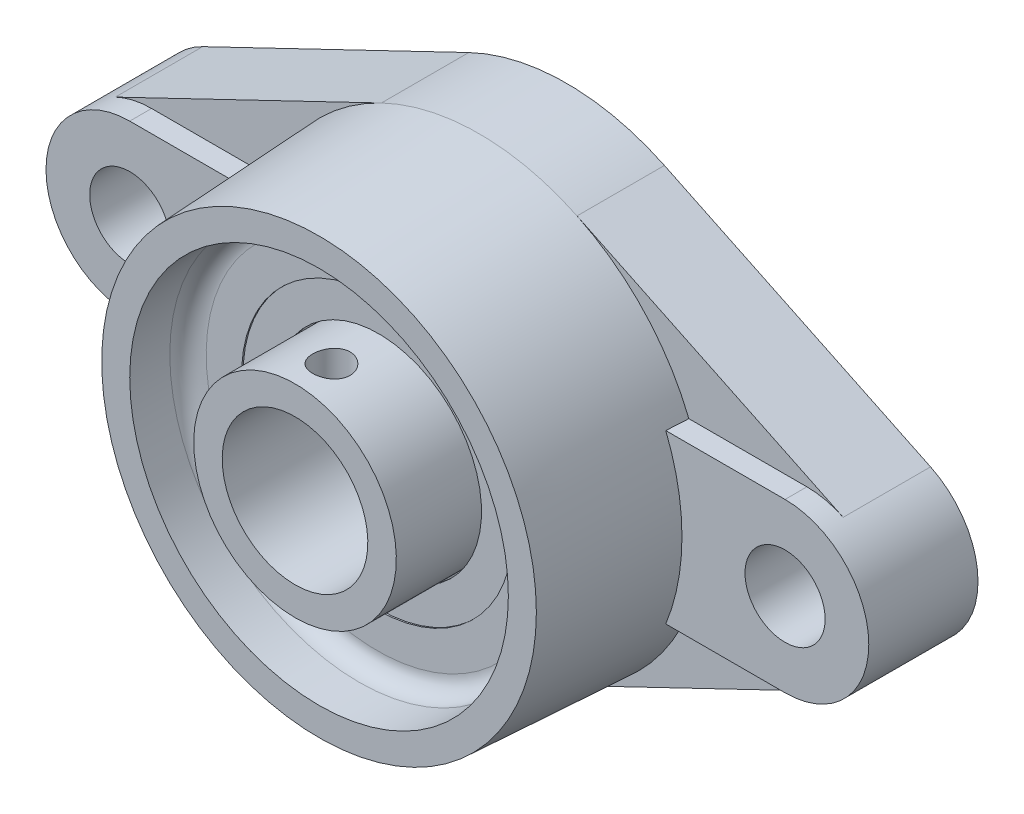
SolidWorks part; units mm, degrees
ref_plane "前视" through (0, 0, 0) normal (0, 0, 1) x (1, 0, 0)
ref_plane "上视" through (0, 0, 0) normal (0, 1, 0) x (1, 0, 0)
ref_plane "右视" through (0, 0, 0) normal (1, 0, 0) x (0, 0, -1)
sketch "尺寸草图" plane through (0, 0, 0) normal (0, 0, 1) x (1, 0, 0)
  line L0 (0, 0) -> (0, -31) construction
  line L1 (0, 0) -> (-56.5, 0) construction
  line L2 (0, 0) -> (47, 0) construction
  line L3 (49, 0) -> (80, 0) construction
  circle A0 centre (0, 0) radius 31
  circle A1 centre (-45, 0) radius 5.5
  point P8 (15, 0)
  point P9 (19, 0)
  point P10 (49, 0)
  point P11 (-14, 0)
  point P14 (50, 0)
  point P15 (67.3, 0)
  point P16 (69, 0)
  point P17 (54, 0)
  point P18 (60, 0)
  dimension "L" = 62
  dimension "N" = 11
  dimension "H" = 113
  dimension "J" = 90
  dimension "Da" = 47
  dimension "A1" = 15
  dimension "A2" = 19
  dimension "A" = 34
  dimension "C" = 14
  dimension "ucB" = 31
  dimension "ucP" = 1
  dimension "ucd" = 20
  dimension "ucG" = 5
  dimension "ucDs" = 6
  dimension "ucS" = 12.7
sketch "草图2" plane through (0, 0, 0) normal (0, 0, 1) x (1, 0, 0)
  line L0 (0, 0) -> (0, -31) construction
  line L1 (0, 0) -> (0, -31) construction
  line L2 (-49.9833, 10.3642) -> (-13.4333, 27.9382)
  line L3 (-49.9833, -10.3642) -> (-13.4333, -27.9382)
  line L4 (0, 0) -> (-56.5, 0) construction
  line L5 (49.9833, 10.3642) -> (13.4333, 27.9382)
  line L6 (49.9833, -10.3642) -> (13.4333, -27.9382)
  circle A0 centre (-45, 0) radius 5.5 construction
  circle A1 centre (0, 0) radius 31 construction
  circle A2 centre (-45, 0) radius 5.5
  arc A3 (13.4333, 27.9382) -> (-13.4333, 27.9382) centre (0, 0) ccw
  circle A4 centre (45, 0) radius 5.5
  arc A5 (-49.9833, 10.3642) -> (-49.9833, -10.3642) centre (-45, 0) ccw
  arc A6 (49.9833, 10.3642) -> (49.9833, -10.3642) centre (45, 0) cw
  arc A7 (-13.4333, -27.9382) -> (13.4333, -27.9382) centre (0, 0) ccw
  dimension "D1" = 113
extrude "基体-拉伸" add sketch "草图2" along normal blind 12
sketch "草图3" plane through (0, 0, 0) normal (0, 0, 1) x (1, 0, 0)
  line L0 (-45, 11.5) -> (45, 11.5)
  line L1 (-45, -11.5) -> (45, -11.5)
  arc A0 (49.9833, -10.3642) -> (49.9833, 10.3642) centre (45, 0) ccw construction
  arc A1 (-49.9833, 10.3642) -> (-49.9833, -10.3642) centre (-45, 0) ccw construction
  arc A2 (45, -11.5) -> (45, 11.5) centre (45, 0) ccw
  arc A3 (-45, 11.5) -> (-45, -11.5) centre (-45, 0) ccw
  circle A4 centre (45, 0) radius 5.5 construction
  circle A5 centre (45, 0) radius 5.5
  circle A6 centre (-45, 0) radius 5.5 construction
  circle A7 centre (-45, 0) radius 5.5
extrude "凸台-拉伸1" add sketch "草图3" along normal blind 15
sketch "草图4" plane through (0, 0, 12) normal (0, 0, 1) x (1, 0, 0)
  circle A0 centre (0, 0) radius 31 construction
  circle A1 centre (0, 0) radius 31
extrude "凸台-拉伸2" add sketch "草图4" along normal blind 22 draft 3
sketch "草图5" plane through (0, 0, 0) normal (0, 0, -1) x (-1, 0, 0)
  line L0 (-34.9601, 11.7401) -> (-11.1497, 23.1887)
  line L1 (-49.9833, 10.3642) -> (-13.4333, 27.9382) construction
  line L2 (0, 31) -> (0, -31) construction
  line L3 (-34.9601, -11.7401) -> (-11.1497, -23.1887)
  line L4 (-45, 0) -> (45, 0) construction
  line L5 (34.9601, -11.7401) -> (11.1497, -23.1887)
  line L6 (34.9601, 11.7401) -> (11.1497, 23.1887)
  arc A0 (11.1497, 23.1887) -> (-11.1497, 23.1887) centre (0, 0) ccw
  arc A1 (-36.0063, 7.1668) -> (-36.0063, -7.1668) centre (-45, 0) cw
  arc A2 (-13.4333, -27.9382) -> (13.4333, -27.9382) centre (0, 0) ccw construction
  arc A3 (-49.9833, 10.3642) -> (-49.9833, -10.3642) centre (-45, 0) ccw construction
  arc A5 (11.1497, -23.1887) -> (-11.1497, -23.1887) centre (0, 0) cw
  arc A6 (-13.4333, -27.9382) -> (13.4333, -27.9382) centre (0, 0) ccw construction
  arc A7 (-36.0063, -7.1668) -> (-34.9601, -11.7401) centre (-33.6601, -9.0364) ccw
  arc A8 (36.0063, 7.1668) -> (34.9601, 11.7401) centre (33.6601, 9.0364) ccw
  arc A9 (-36.0063, 7.1668) -> (-34.9601, 11.7401) centre (-33.6601, 9.0364) cw
  arc A10 (36.0063, -7.1668) -> (34.9601, -11.7401) centre (33.6601, -9.0364) cw
  arc A11 (36.0063, 7.1668) -> (36.0063, -7.1668) centre (45, 0) ccw
  dimension "D1" = 25.73
  dimension "D2" = 3
extrude "切除-拉伸2" cut sketch "草图5" against normal blind 3
sketch "草图6" plane through (0, 0, 0) normal (1, 0, 0) x (0, 0, -1)
  line L0 (-34, 29.847) -> (-34, -29.847) construction
  line L1 (-36, 26) -> (-28.5, 26)
  line L2 (-9.5, 26) -> (2, 26)
  line L3 (-26, 22.4332) -> (-26, 23.5)
  line L4 (-23.6667, 25.2678) -> (-21.3333, 25.2678)
  line L5 (-23.6667, 25.2678) -> (-23.6667, 23.032)
  line L6 (-12, 22.4332) -> (-12, 23.5)
  line L7 (-21.3333, 25.2678) -> (-21.3333, 23.3839)
  line L8 (0, 0) -> (-34, 0) construction
  line L9 (-36, 26) -> (-36, 0)
  line L10 (-36, 0) -> (2, 0)
  line L11 (2, 0) -> (2, 26)
  line L12 (0, 10.3642) -> (0, 27.9382) construction
  line L13 (0, 27.9382) -> (0, 31) construction
  arc A0 (-26, 22.4332) -> (-23.6667, 23.032) centre (-19, 0) cw
  arc A1 (-21.3333, 23.3839) -> (-12, 22.4332) centre (-19, 0) cw
  arc A2 (-28.5, 26) -> (-26, 23.5) centre (-28.5, 23.5) cw
  arc A3 (-9.5, 26) -> (-12, 23.5) centre (-9.5, 23.5) ccw
  point P16 (-19, 23.5)
  point P17 (-26.7322, 25.2678)
  dimension "D3" = 23.5
  dimension "D1" = 19
  dimension "D2" = 14
  dimension "D4" = 26
  dimension "D5" = 2
  dimension "D6" = 2
revolve "切除-旋转1" cut sketch "草图6" angle 360 about L8
ref_plane "油嘴用面" through (0, 0, 18.5) normal (0, 0, 1) x (1, 0, 0)
sketch "草图7" plane through (0, 0, 18.5) normal (0, 0, 1) x (1, 0, 0)
  line L0 (-26.9827, -26.9827) -> (0, 0) construction
  line L2 (-21.6794, -21.6794) -> (-18.8509, -24.5079)
  line L3 (-18.8509, -24.5079) -> (-19.1566, -24.8137)
  line L4 (-25.4554, -27.5767) -> (-26.0494, -26.9827)
  line L5 (-26.9827, -26.9827) -> (-21.6794, -21.6794)
  line L6 (0, 0) -> (-22.4332, 0) construction
  circle A1 centre (0, 0) radius 22.4332 construction
  arc A4 (-19.1566, -24.8137) -> (-20.5217, -26.6375) centre (-13.4998, -30.4705) ccw
  arc A5 (-20.5217, -26.6375) -> (-25.4554, -27.5767) centre (-23.3744, -25.0803) cw
  arc A6 (-26.9827, -26.9827) -> (-26.0494, -26.9827) centre (-26.516, -26.516) ccw
  dimension "D4" = 8
  dimension "D5" = 3.25
  dimension "D7" = 0.66
  dimension "D1" = 1.5
  dimension "D2" = 4.0001
  dimension "D3" = 0.4323
  dimension "D6" = 45
  dimension "D8" = 7.5
  dimension "D9" = 30.6593
revolve "凸台-旋转1" add sketch "草图7" angle 360 about L5
sketch "草图8" plane through (0, 0, 0) normal (1, 0, 0) x (0, 0, -1)
  line L0 (-26, 22.4332) -> (-26, 18.64)
  line L1 (-26, 18.64) -> (-12, 18.64)
  line L2 (-12, 18.64) -> (-12, 22.4332)
  line L3 (-19, 0) -> (0, 0) construction
  arc A0 (-26, 22.4332) -> (-12, 22.4332) centre (-19, 0) cw
  arc A1 (-12, 22.4332) -> (-21.3333, 23.3839) centre (-19, 0) ccw construction
  dimension "D2" = 4.86
  dimension "D1" = 14
revolve "凸台-旋转2" add sketch "草图8" angle 360 about L3
sketch "草图9" plane through (0, 0, 0) normal (1, 0, 0) x (0, 0, -1)
  line L0 (-19, 0) -> (-19, 23.5) construction
  line L1 (-34, 0) -> (0, 0) construction
  line L2 (-19, 20.5975) -> (-19, 12.9025)
  line L3 (-34, 29.847) -> (-34, -29.847) construction
  arc A0 (-12, 22.4332) -> (-26, 22.4332) centre (-19, 0) ccw construction
  arc A1 (-19, 12.9025) -> (-19, 20.5975) centre (-19, 16.75) ccw
  dimension "D1" = 3.8475
  dimension "D3" = 33.5
  dimension "D2" = 6.75
revolve "凸台-旋转3" add sketch "草图9" angle 360 about L0
pattern_circular "阵列(圆周)1" count 2 over 360 about axis through (0, 0, 0) along (0, 0, 1) of "凸台-旋转3"
sketch "草图11" plane through (0, 0, 0) normal (1, 0, 0) x (0, 0, -1)
  line L0 (-19, 0) -> (0, 0) construction
  line L1 (-37.3, 13.915) -> (-6.3, 13.915)
  line L2 (-37.3, 13.915) -> (-37.3, 10)
  line L3 (-37.3, 10) -> (-6.3, 10)
  line L4 (-6.3, 13.915) -> (-6.3, 10)
  dimension "D1" = 20
  dimension "D2" = 3.915
  dimension "D3" = 12.7
  dimension "D4" = 31
revolve "凸台-旋转4" add sketch "草图11" angle 360 about L0
sketch "草图12" plane through (0, 0, 0) normal (1, 0, 0) x (0, 0, -1)
  line L0 (-21.6012, 13.915) -> (-37.3, 13.915) construction
  line L1 (-25.8, 18.84) -> (-25.6, 18.84)
  line L2 (-25.8, 18.84) -> (-25.8, 14.115)
  line L3 (-25.8, 14.115) -> (-25.6, 14.115)
  line L4 (-25.6, 18.84) -> (-25.6, 14.115)
  line L5 (-12.4, 18.84) -> (-12.2, 18.84)
  line L6 (-12.4, 18.84) -> (-12.4, 14.115)
  line L7 (-12.4, 14.115) -> (-12.2, 14.115)
  line L8 (-12.2, 18.84) -> (-12.2, 14.115)
  line L9 (-22.3513, 18.64) -> (-26, 18.64) construction
  line L10 (-26, 23.5) -> (-26, -23.5) construction
  line L11 (-12, -23.5) -> (-12, 23.5) construction
  line L12 (0, 0) -> (-34, 0) construction
  line L13 (-12, 0) -> (-34, 0) construction
  line L14 (-34, 29.847) -> (-34, -29.847) construction
  dimension "D1" = 0.2
  dimension "D2" = 0.2
  dimension "D3" = 0.2
  dimension "D4" = 0.2
  dimension "D5" = 0.2
revolve "凸台-旋转5" add sketch "草图12" angle 360 about L12
sketch "草图13" plane through (0, 0, 0) normal (1, 0, 0) x (0, 0, -1)
  line L0 (-32.3, 15.915) -> (-32.3, 0) construction
  line L1 (-32.3, 15.915) -> (-29.733, 15.915)
  line L2 (-29.733, 15.915) -> (-29.733, 0)
  line L3 (-29.733, 0) -> (-32.3, 0)
  line L5 (-37.3, 13.915) -> (-37.3, -13.915) construction
  line L6 (-21.6012, 13.915) -> (-37.3, 13.915) construction
  line L7 (-32.3, 15.915) -> (-32.3, 0)
  dimension "D1" = 5
  dimension "D2" = 5.134
  dimension "D3" = 2
revolve "切除-旋转2" cut sketch "草图13" angle 360 about L0
cosmetic thread "装饰螺纹线1"
